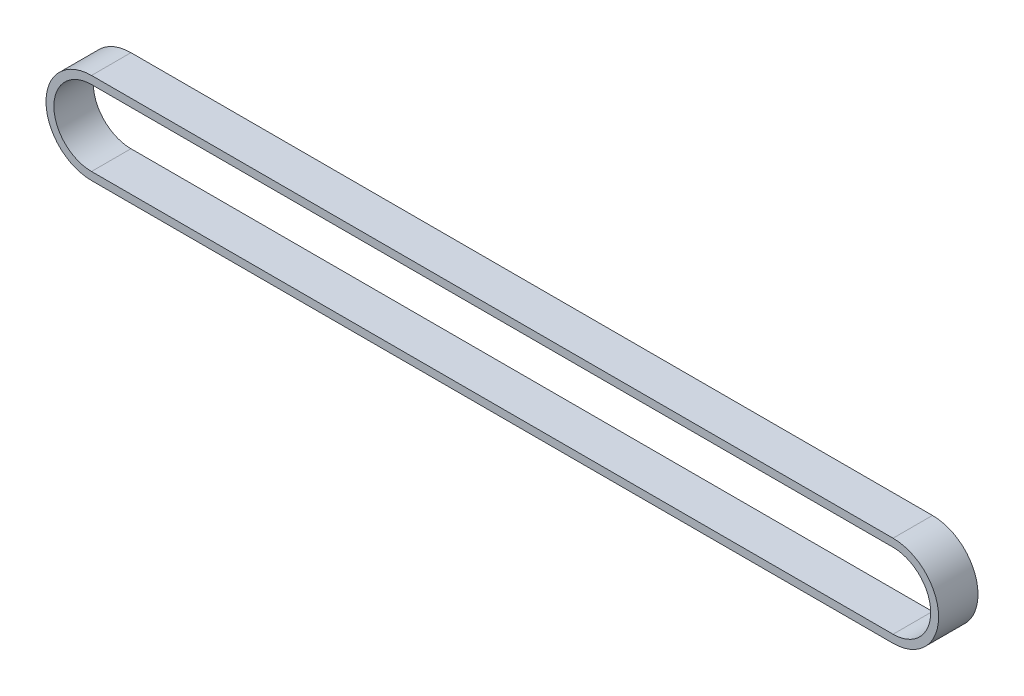
SolidWorks part; units mm, degrees
material "NEOPRENE"
ref_plane "Front" through (0, 0, 0) normal (0, 0, 1) x (1, 0, 0)
ref_plane "Top" through (0, 0, 0) normal (0, 1, 0) x (1, 0, 0)
ref_plane "Right" through (0, 0, 0) normal (1, 0, 0) x (0, 0, -1)
sketch "Sketch2" plane through (0, 0, 0) normal (0, 0, 1) x (1, 0, 0)
  line L0 (0, 0) -> (1, 0) construction
  line L1 (0, 0) -> (0, 1) construction
  line L2 (-304.9967, 14.325) -> (0, 14.325)
  line L3 (0, -14.325) -> (-304.9967, -14.325)
  arc A0 (-304.9967, -14.325) -> (-304.9967, 14.325) centre (-304.9967, 0) cw
  arc A1 (0, 14.325) -> (0, -14.325) centre (0, 0) cw
extrude "Extrude-Thin1" add sketch "Sketch2" along normal mid plane 15 thin thin type one direction wall 3
